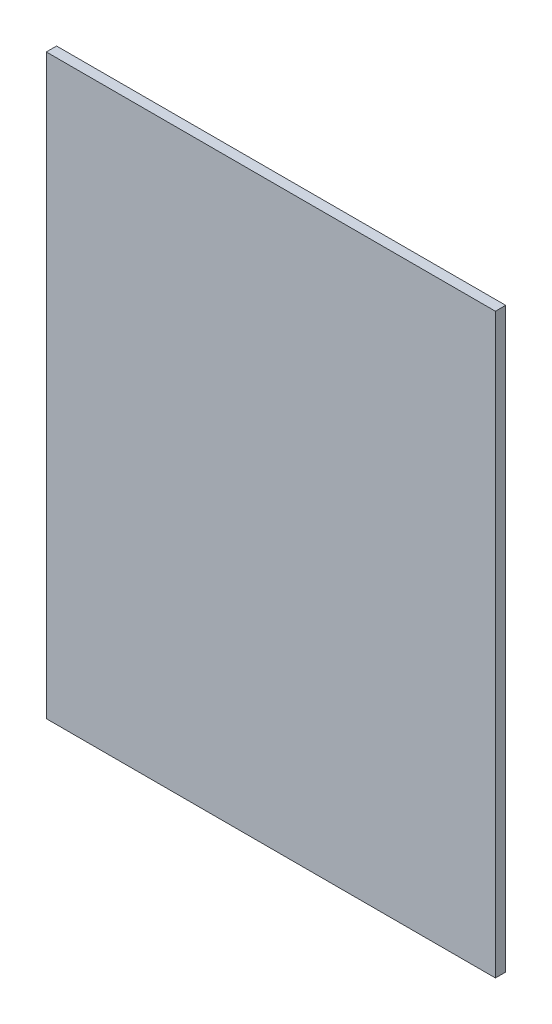
SolidWorks part; units mm, degrees
ref_plane "Front Plane" through (0, 0, 0) normal (0, 0, 1) x (1, 0, 0)
ref_plane "Top Plane" through (0, 0, 0) normal (0, 1, 0) x (1, 0, 0)
ref_plane "Right Plane" through (0, 0, 0) normal (1, 0, 0) x (0, 0, -1)
ref_plane "Plane1" through (0, 0, 9) normal (0, 0, 1) x (1, 0, 0)
sketch "Sketch1" plane through (0, 0, 9) normal (0, 0, 1) x (1, 0, 0)
  line L1 (-35, -12.5) -> (35, -12.5)
  line L2 (-35, -12.5) -> (-35, 77.5)
  line L3 (-35, 77.5) -> (35, 77.5)
  line L4 (35, -12.5) -> (35, 77.5)
  line L5 (-35, -12.5) -> (35, 77.5) construction
  line L6 (-35, 77.5) -> (35, -12.5) construction
  point P0 (0, 32.5)
extrude "Boss-Extrude1" add sketch "Sketch1" along normal blind 1.6
